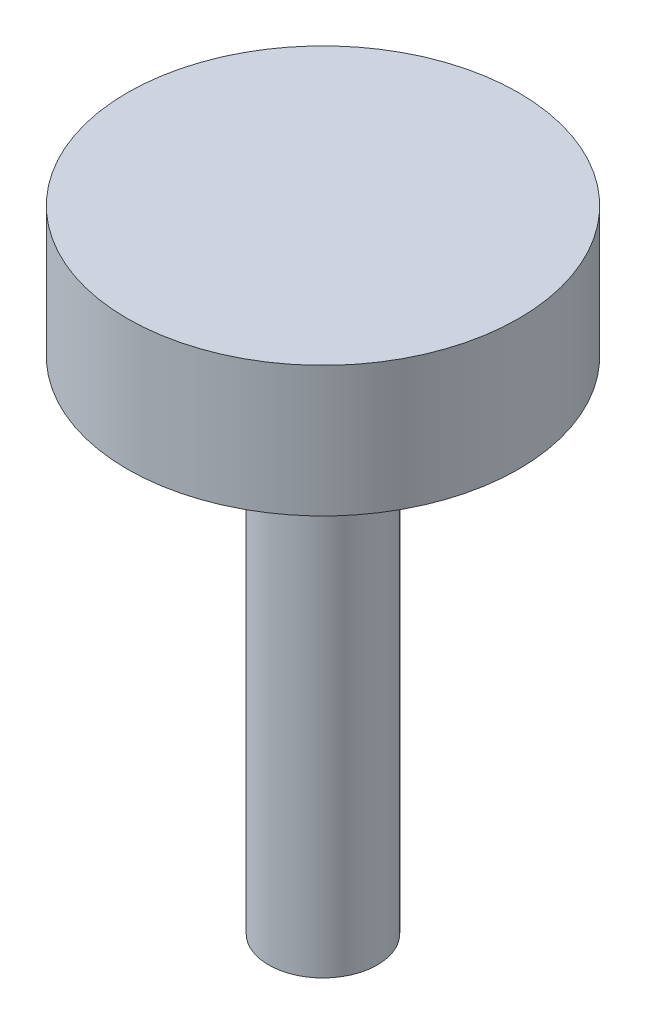
SolidWorks part; units mm, degrees
ref_plane "Front Plane" through (0, 0, 0) normal (0, 0, 1) x (1, 0, 0)
ref_plane "Top Plane" through (0, 0, 0) normal (0, 1, 0) x (1, 0, 0)
ref_plane "Right Plane" through (0, 0, 0) normal (1, 0, 0) x (0, 0, -1)
sketch "Sketch1" plane through (0, 0, 0) normal (0, 1, 0) x (1, 0, 0)
  circle A0 centre (0, 0) radius 45
extrude "Boss-Extrude1" add sketch "Sketch1" along normal blind 30
sketch "Sketch2" plane through (0, 0, 0) normal (0, -1, 0) x (1, 0, 0)
  circle A0 centre (0, 0) radius 12.5
  dimension "D1" = 25
extrude "Boss-Extrude2" add sketch "Sketch2" along normal blind 115 contours A0
